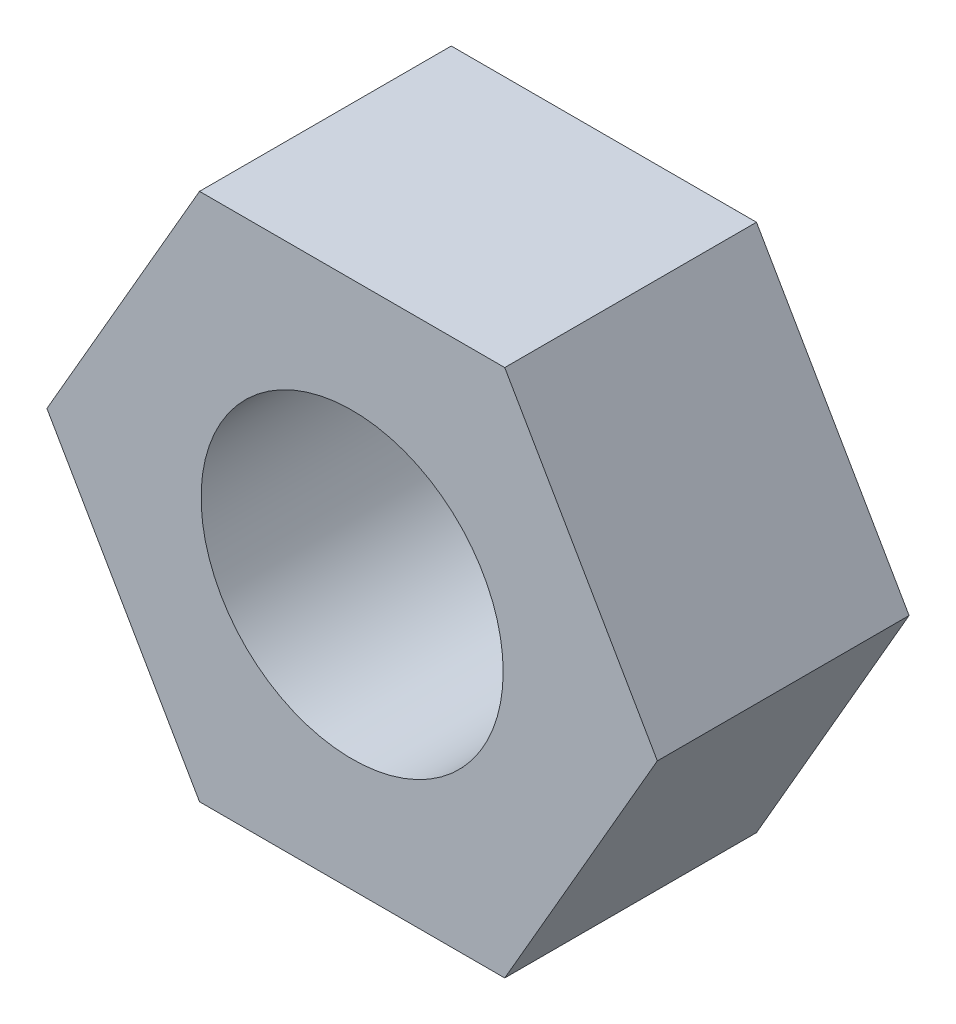
SolidWorks part; units mm, degrees
material "Chrome Stainless Steel"
ref_plane "Front Plane" through (0, 0, 0) normal (0, 0, 1) x (1, 0, 0)
ref_plane "Top Plane" through (0, 0, 0) normal (0, 1, 0) x (1, 0, 0)
ref_plane "Right Plane" through (0, 0, 0) normal (1, 0, 0) x (0, 0, -1)
sketch "Sketch1" plane through (0, 0, 0) normal (0, 0, 1) x (1, 0, 0)
  line L1 (6.0622, 0) -> (3.0311, 5.25)
  line L2 (3.0311, 5.25) -> (-3.0311, 5.25)
  line L3 (-3.0311, 5.25) -> (-6.0622, 0)
  line L4 (-6.0622, 0) -> (-3.0311, -5.25)
  line L5 (-3.0311, -5.25) -> (3.0311, -5.25)
  line L6 (3.0311, -5.25) -> (6.0622, 0)
  circle A0 centre (0, 0) radius 5.25 construction
  circle A1 centre (0, 0) radius 3
  dimension "D2" = 6
  dimension "D1" = 10.5
extrude "Boss-Extrude1" add sketch "Sketch1" along normal blind 5
